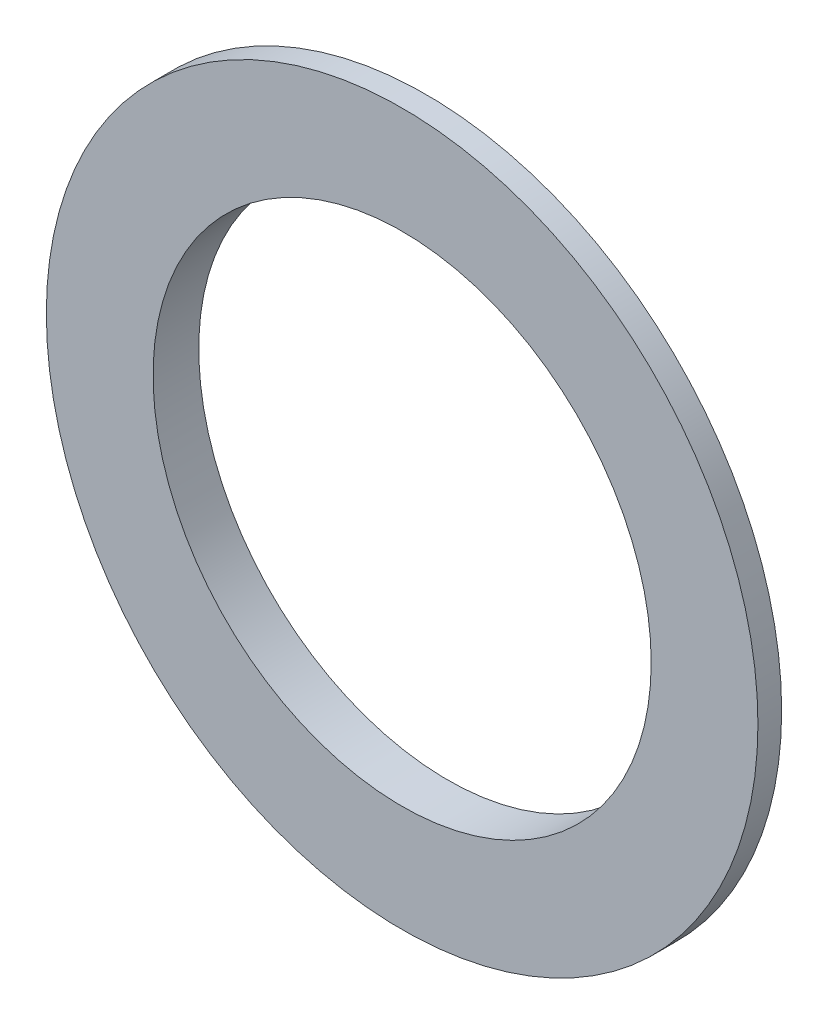
SolidWorks part; units mm, degrees
ref_plane "Plano frontal" through (0, 0, 0) normal (0, 0, 1) x (1, 0, 0)
ref_plane "Plano superior" through (0, 0, 0) normal (0, 1, 0) x (1, 0, 0)
ref_plane "Plano direito" through (0, 0, 0) normal (1, 0, 0) x (0, 0, -1)
sketch "Esboço1" plane through (0, 0, 0) normal (0, 0, 1) x (1, 0, 0)
  circle A0 centre (0, 0) radius 22 construction
  circle A1 centre (0, 0) radius 23.5 construction
  circle A2 centre (0, 0) radius 25 construction
  dimension "D1" = 50
sketch "Esboço2" plane through (0, 0, 0) normal (0, 0, 1) x (1, 0, 0)
  circle A0 centre (0, 0) radius 21
  circle A3 centre (0, 0) radius 22.35
  circle A5 centre (0, 0) radius 25 construction
  dimension "D2" = 4
  dimension "D1" = 1.35
extrude "Ressalto-extrusão1" add sketch "Esboço2" along normal blind 1.85
sketch "Esboço3" plane through (0, 0, 1.85) normal (0, 0, 1) x (1, 0, 0)
  circle A0 centre (0, 0) radius 30
  circle A1 centre (0, 0) radius 25 construction
  circle A4 centre (0, 0) radius 21 construction
  circle A5 centre (0, 0) radius 21
  dimension "D1" = 5
extrude "Ressalto-extrusão2" add sketch "Esboço3" along normal blind 2
